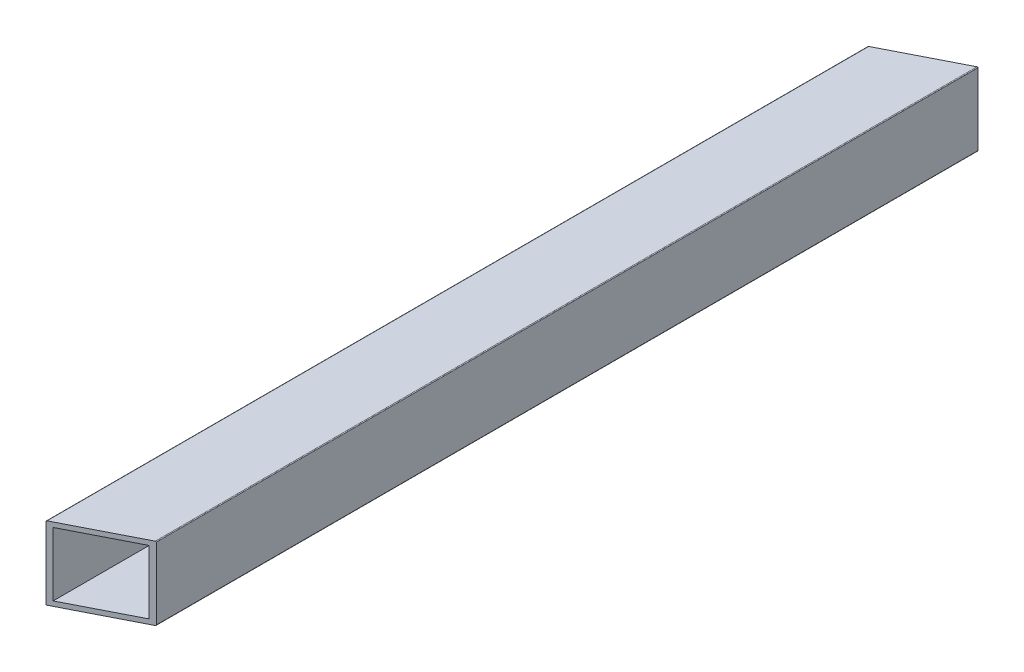
SolidWorks part; units mm, degrees
material "6061 Alloy"
ref_plane "Front Plane" through (0, 0, 0) normal (0, 0, 1) x (1, 0, 0)
ref_plane "Top Plane" through (0, 0, 0) normal (0, 1, 0) x (1, 0, 0)
ref_plane "Right Plane" through (0, 0, 0) normal (1, 0, 0) x (0, 0, -1)
sketch "Sketch1" plane through (0, 0, 0) normal (0, 0, 1) x (1, 0, 0)
  line L1 (-12.7, -12.7) -> (12.7, -12.7)
  line L2 (-12.7, -12.7) -> (-12.7, 12.7)
  line L3 (-12.7, 12.7) -> (12.7, 12.7)
  line L4 (12.7, -12.7) -> (12.7, 12.7)
  line L5 (-12.7, -12.7) -> (12.7, 12.7) construction
  line L6 (-12.7, 12.7) -> (12.7, -12.7) construction
  point P0 (0, 0)
  dimension "D1" = 25.4
  dimension "D2" = 25.4
extrude "Boss-Extrude1" add sketch "Sketch1" along normal mid plane 298.45 contours L2 L1 L4 L3
fillet "Fillet1" radius 0.254 4 edges at (-12.7, -12.7, 0) (12.7, -12.7, 0) (-12.7, 12.7, 0) (12.7, 12.7, 0)
sketch "Sketch2" plane through (0, -12.7, 0) normal (0, -1, 0) x (1, 0, 0)
  line L0 (-12.7, 149.225) -> (12.7, 136.2831)
  line L1 (12.7, 149.225) -> (12.7, -149.225) construction
  line L2 (-12.446, 149.225) -> (12.446, 149.225) construction
  line L3 (12.7, 136.2831) -> (12.7, 149.225)
  line L4 (12.7, 149.225) -> (-12.7, 149.225)
  dimension "D1" = 27
extrude "Cut-Extrude1" cut sketch "Sketch2" against normal blind 38.1 contours L4 L0 L3
sketch "Sketch3" plane through (0, -12.7, 0) normal (0, -1, 0) x (1, 0, 0)
  line L0 (12.7, -149.225) -> (-12.7, -136.2831)
  line L1 (-12.7, -149.225) -> (-12.7, 149.225) construction
  line L2 (-12.446, -149.225) -> (12.446, -149.225) construction
  line L3 (12.7, -149.225) -> (-12.7, -149.225)
  line L4 (-12.7, -149.225) -> (-12.7, -136.2831)
  dimension "D1" = 27
sketch "Sketch4" plane through (0, 0, -149.225) normal (0, 0, -1) x (-1, 0, 0)
  line L0 (12.446, 12.7) -> (-12.446, 12.7) construction
  line L1 (-11.049, -11.049) -> (11.049, -11.049)
  line L2 (-11.049, -11.049) -> (-11.049, 11.049)
  line L3 (-11.049, 11.049) -> (11.049, 11.049)
  line L4 (11.049, -11.049) -> (11.049, 11.049)
  line L5 (-11.049, -11.049) -> (11.049, 11.049) construction
  line L6 (-11.049, 11.049) -> (11.049, -11.049) construction
  line L7 (-12.7, -12.446) -> (-12.7, 12.446) construction
  point P0 (0, 0)
  dimension "D1" = 1.651
  dimension "D2" = 1.651
extrude "Cut-Extrude4" cut sketch "Sketch4" against normal blind 685.8 contours L2 L1 L4 L3
sketch "Sketch5" plane through (0, -12.7, 0) normal (0, -1, 0) x (1, 0, 0)
  line L0 (-12.7, -136.2831) -> (-12.7, -149.225)
  line L1 (-12.7, -149.225) -> (12.7, -149.225)
  line L2 (12.7, -149.225) -> (-12.7, -136.2831)
extrude "Cut-Extrude5" cut sketch "Sketch5" against normal blind 685.8
